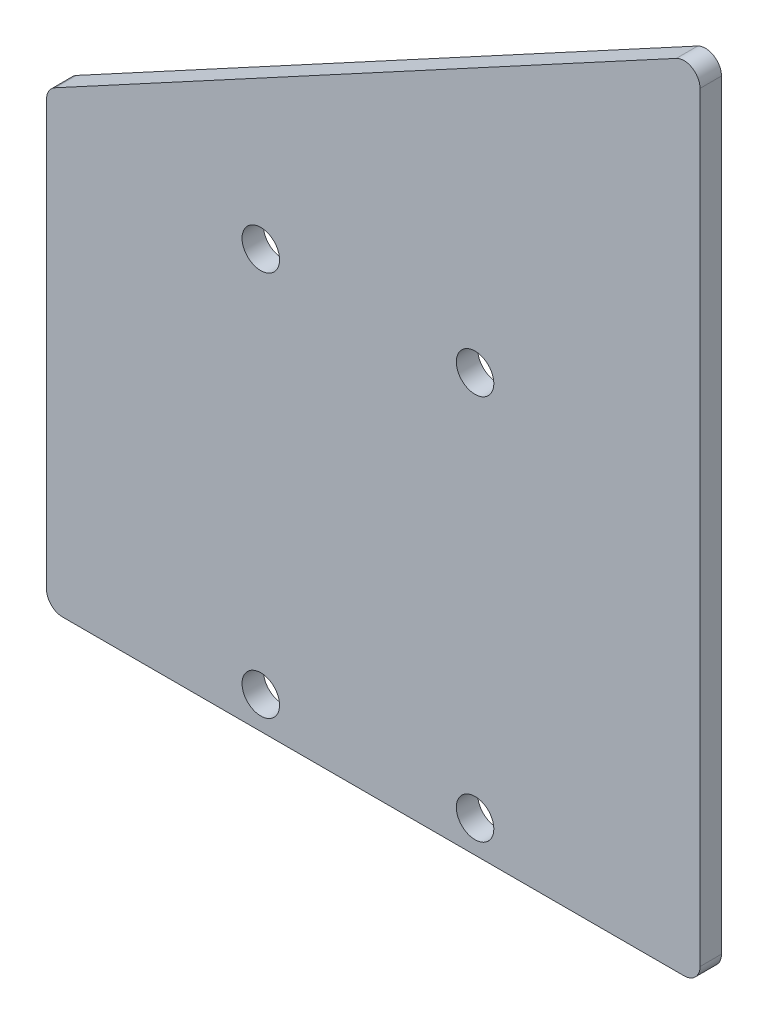
SolidWorks part; units mm, degrees
ref_plane "前视基准面" through (0, 0, 0) normal (0, 0, 1) x (1, 0, 0)
ref_plane "上视基准面" through (0, 0, 0) normal (0, 1, 0) x (1, 0, 0)
ref_plane "右视基准面" through (0, 0, 0) normal (1, 0, 0) x (0, 0, -1)
sketch "草图1" plane through (0, 0, 0) normal (0, 0, 1) x (1, 0, 0)
  line L0 (0, 3) -> (20, 3) construction
  line L1 (0, 0) -> (61, 0)
  line L2 (0, 0) -> (0, 42)
  line L3 (0, 42) -> (61, 42)
  line L4 (61, 0) -> (61, 42)
  line L5 (20, 3) -> (40, 3) construction
  line L6 (0, 21) -> (61, 21) construction
  circle A0 centre (20, 3) radius 1.75
  circle A1 centre (40, 3) radius 1.75
  circle A2 centre (40, 39) radius 1.75
  circle A3 centre (20, 39) radius 1.75
  dimension "D6" = 3.5
  dimension "D1" = 61
  dimension "D2" = 42
  dimension "D3" = 20
  dimension "D4" = 20
  dimension "D5" = 3
extrude "凸台-拉伸1" add sketch "草图1" along normal blind 2
sketch "草图2" plane through (0, 0, 2) normal (0, 0, 1) x (1, 0, 0)
  line L0 (61, 75) -> (0, 42)
  line L1 (0, 42) -> (61, 42)
  line L2 (61, 42) -> (61, 75)
  dimension "D1" = 33
extrude "凸台-拉伸2" add sketch "草图2" against normal up to surface (2 mm away) up to face at (38.25, 39, 0)
sketch "草图3" plane through (0, 0, 2) normal (0, 0, 1) x (1, 0, 0)
  line L4 (0, 42) -> (0, 0)
  line L5 (0, 0) -> (61, 0)
  line L6 (61, 0) -> (61, 75)
  line L7 (61, 75) -> (0, 42)
  line L8 (0, 41.106) -> (0, 1.5)
  line L9 (1.5, 0) -> (59.5, 0)
  line L10 (61, 1.5) -> (61, 72.4831)
  line L11 (58.7863, 73.8024) -> (0.7863, 42.4254)
  arc A0 (61, 72.4831) -> (58.7863, 73.8024) centre (59.5, 72.4831) ccw
  arc A1 (59.5, 0) -> (61, 1.5) centre (59.5, 1.5) ccw
  arc A2 (0, 1.5) -> (1.5, 0) centre (1.5, 1.5) ccw
  arc A3 (0, 41.106) -> (0.7863, 42.4254) centre (1.5, 41.106) cw
  dimension "D2" = 1.5
  dimension "D1" = 0
extrude "切除-拉伸1" cut sketch "草图3" against normal blind 10 flip side to cut
